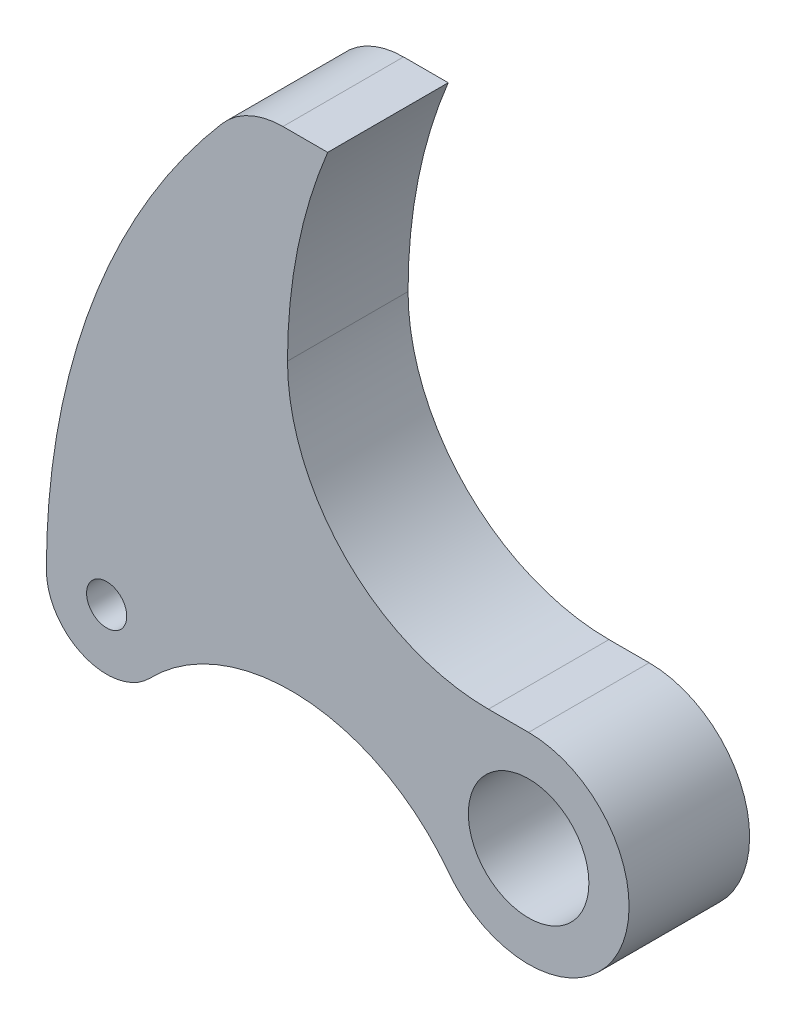
SolidWorks part; units mm, degrees
ref_plane "Alzado" through (0, 0, 0) normal (0, 0, 1) x (1, 0, 0)
ref_plane "Planta" through (0, 0, 0) normal (0, 1, 0) x (1, 0, 0)
ref_plane "Vista lateral" through (0, 0, 0) normal (1, 0, 0) x (0, 0, -1)
sketch "Croquis2" plane through (0, 0, 0) normal (0, 0, 1) x (1, 0, 0)
  line L0 (-10, 0) -> (10, 0) construction
  line L1 (10, 0) -> (10, 30) construction
  line L2 (10, 50) -> (-10, 50) construction
  line L3 (-10, 50) -> (-10, 0) construction
  line L4 (0, 50) -> (0, 40) construction
  line L5 (-10, 25) -> (-5, 25) construction
  line L6 (-5, 25) -> (-5, 45) construction
  line L7 (5, 45) -> (5, 50) construction
  line L8 (0, 40) -> (-5, 40) construction
  line L9 (0, 0) -> (0, 2) construction
  line L10 (-5, 45) -> (-5, 50) construction
  line L11 (6, 7) -> (-6, 7) construction
  line L12 (-6, 7) -> (-6, 30) construction
  line L13 (-10.5, 37.5) -> (-12, 37.5) construction
  line L14 (0, 37.5) -> (-10.5, 37.5) construction
  line L15 (0, 2) -> (0, 4) construction
  line L16 (0, 4) -> (0, 7) construction
  line L17 (-10, 0) -> (-10, 7) construction
  line L18 (-10, 0) -> (10, 0) construction
  line L19 (0, 30) -> (0, 33) construction
  line L20 (5, 45) -> (5, 50) construction
  line L21 (-5, 45) -> (-6, 45) construction
  line L22 (5, 50) -> (7, 50) construction
  line L23 (-6, 35) -> (-6, 30) construction
  line L24 (-6, 35) -> (-6, 30) construction
  line L25 (7, 50) -> (7, 43) construction
  line L26 (-6, 30) -> (6, 30) construction
  line L27 (6, 30) -> (6, 7) construction
  line L28 (6, 7) -> (-10, 7) construction
  line L29 (0, 24) -> (-10.5, 24) construction
  line L30 (0, 30) -> (0, 24) construction
  line L31 (-6, 45) -> (-1, 45) construction
  line L32 (-1, 40) -> (0, 40)
  line L33 (-5, 50) -> (-6.1129, 50)
  line L34 (-10.5, 24) -> (-10.5, 37.5) construction
  line L36 (0, 37.5) -> (10.5, 37.5) construction
  arc A0 (0, 40) -> (5, 45) centre (0, 45) ccw construction
  circle A1 centre (0, 37.5) radius 1.5
  arc A2 (-1.9959, 35.9945) -> (0, 40) centre (0, 37.5) ccw
  arc A3 (7, 43) -> (10, 40) centre (10, 43) ccw construction
  circle A4 centre (0, 33) radius 1 construction
  circle A5 centre (0, 4) radius 1 construction
  arc A6 (-6, 45) -> (-1, 40) centre (-1, 45) ccw
  circle A7 centre (-10.5, 37.5) radius 0.5
  arc A8 (-12, 37.5) -> (-9.4234, 36.4556) centre (-10.5, 37.5) ccw
  arc A9 (-7.6308, 49.3023) -> (-12, 37.5) centre (6.125, 37.5) ccw
  arc A10 (-5, 50) -> (-6, 45) centre (7, 45) ccw
  arc A11 (-9.4234, 36.4556) -> (-1.9959, 35.9945) centre (-5.9071, 33.0443) cw
  arc A12 (-6.1129, 50) -> (-7.6308, 49.3023) centre (-6.1129, 48) ccw
  spline S0 degree 3 poles (10, 40) (13.3825, 40) (10, 31.6044) (10, 30) knots 0 0 0 0 1 1 1 1 construction
  point P53 (-7, 50)
  dimension "D3" = 2
  dimension "D1" = 50
  dimension "D2" = 20
extrude "Saliente-Extruir1" add sketch "Croquis2" along normal blind 3
